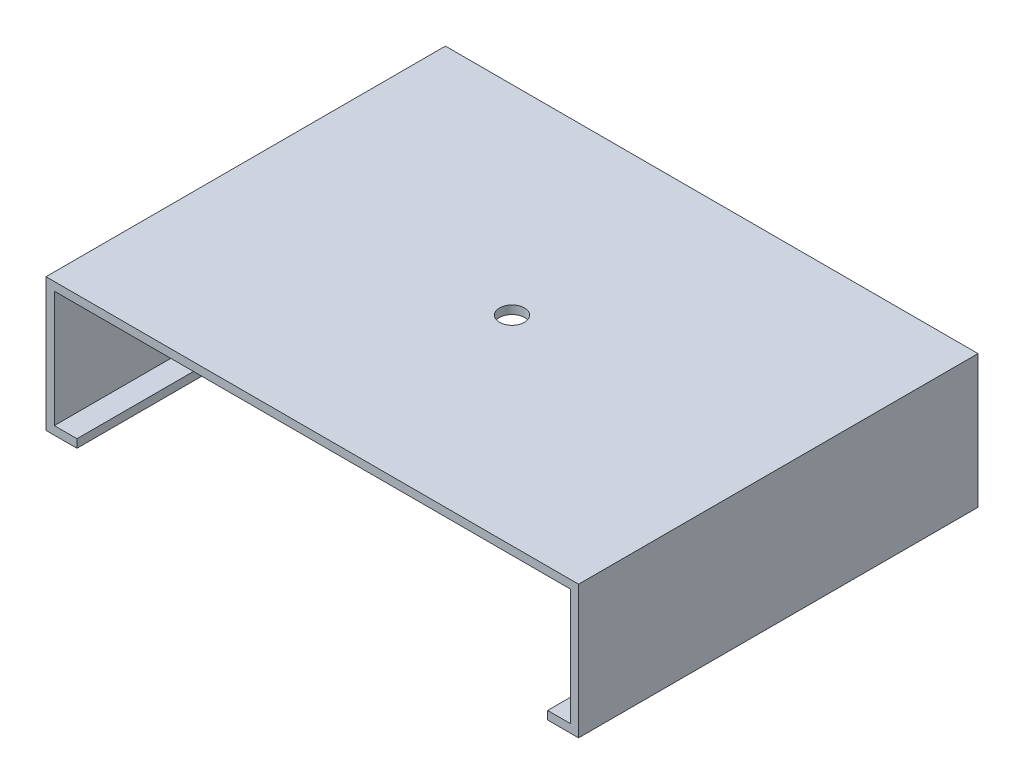
SolidWorks part; units mm, degrees
ref_plane "Front" through (0, 0, 0) normal (0, 0, 1) x (1, 0, 0)
ref_plane "Top" through (0, 0, 0) normal (0, 1, 0) x (1, 0, 0)
ref_plane "Right" through (0, 0, 0) normal (1, 0, 0) x (0, 0, -1)
sketch "Sketch1" plane through (0, 0, 0) normal (0, 0, 1) x (1, 0, 0)
  line L1 (-101.6, 25.4) -> (101.6, 25.4)
  line L2 (-101.6, 25.4) -> (-101.6, -25.4)
  line L3 (-101.6, -25.4) -> (101.6, -25.4)
  line L4 (101.6, 25.4) -> (101.6, -25.4)
  line L5 (-101.6, 25.4) -> (101.6, -25.4) construction
  line L6 (-101.6, -25.4) -> (101.6, 25.4) construction
  line L7 (-98.425, 22.225) -> (98.425, 22.225)
  line L8 (-98.425, 22.225) -> (-98.425, -22.225)
  line L9 (-98.425, -22.225) -> (98.425, -22.225)
  line L10 (98.425, 22.225) -> (98.425, -22.225)
  line L11 (-98.425, 22.225) -> (98.425, -22.225) construction
  line L12 (-98.425, -22.225) -> (98.425, 22.225) construction
  point P0 (0, 0)
  point P6 (0, 0)
  dimension "D1" = 3.175
  dimension "D2" = 3.175
  dimension "D3" = 50.8
  dimension "D4" = 203.2
extrude "Boss-Extrude1" add sketch "Sketch1" along normal blind 152.4
sketch "Sketch2" plane through (0, -25.4, 0) normal (0, -1, 0) x (1, 0, 0)
  line L0 (0, 0) -> (0, 152.4) construction
  line L1 (-101.6, 0) -> (101.6, 0) construction
  line L2 (-101.6, 152.4) -> (101.6, 152.4) construction
  line L4 (-89.789, 0) -> (89.789, 0)
  line L5 (-89.789, 0) -> (-89.789, 152.4)
  line L6 (-89.789, 152.4) -> (89.789, 152.4)
  line L7 (89.789, 0) -> (89.789, 152.4)
  line L8 (-89.789, 0) -> (89.789, 152.4) construction
  line L9 (-89.789, 152.4) -> (89.789, 0) construction
  point P6 (0, 76.2)
  dimension "D1" = 8.636
extrude "Cut-Extrude1" cut sketch "Sketch2" against normal up to surface (3.175 mm away) up to face at (0, -22.225, 76.2)
sketch "Sketch3" plane through (0, 25.4, 0) normal (0, 1, 0) x (1, 0, 0)
  line L0 (0, -152.4) -> (0, 0) construction
  line L1 (101.6, -152.4) -> (-101.6, -152.4) construction
  line L2 (101.6, 0) -> (-101.6, 0) construction
  circle A0 centre (0, -76.2) radius 4.7625
  dimension "D1" = 9.525
extrude "Cut-Extrude2" cut sketch "Sketch3" against normal through all
